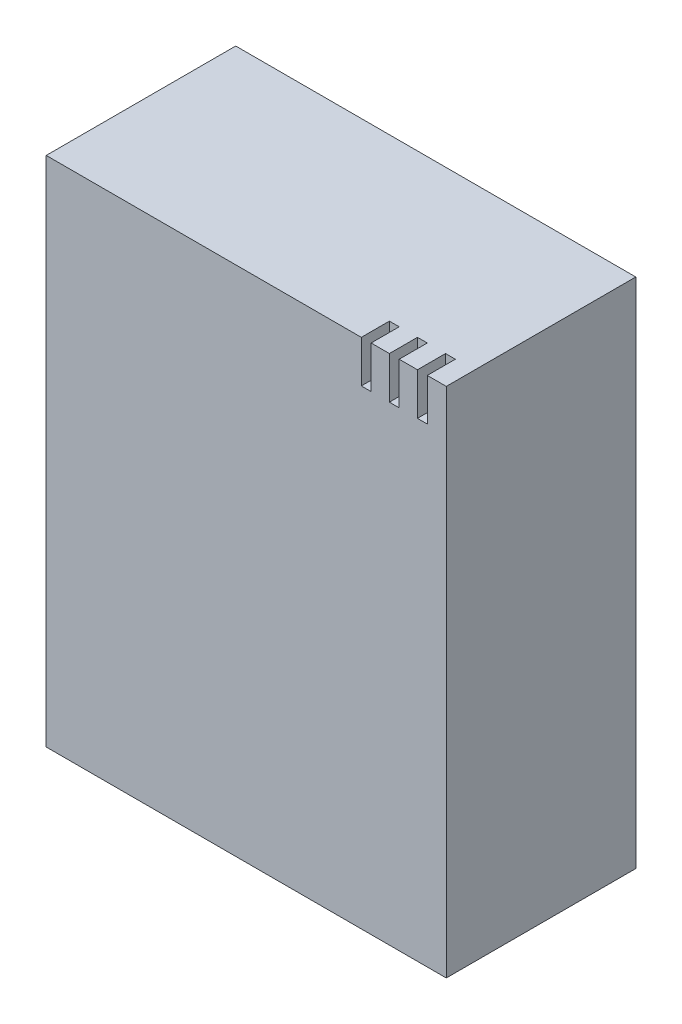
SolidWorks part; units mm, degrees
ref_plane "Front Plane" through (0, 0, 0) normal (0, 0, 1) x (1, 0, 0)
ref_plane "Top Plane" through (0, 0, 0) normal (0, 1, 0) x (1, 0, 0)
ref_plane "Right Plane" through (0, 0, 0) normal (1, 0, 0) x (0, 0, -1)
sketch "Sketch1" plane through (0, 0, 0) normal (0, 1, 0) x (1, 0, 0)
  line L1 (-14.25, -6.75) -> (14.25, -6.75)
  line L2 (-14.25, -6.75) -> (-14.25, 6.75)
  line L3 (-14.25, 6.75) -> (14.25, 6.75)
  line L4 (14.25, -6.75) -> (14.25, 6.75)
  line L5 (-14.25, -6.75) -> (14.25, 6.75) construction
  line L6 (-14.25, 6.75) -> (14.25, -6.75) construction
  point P0 (0, 0)
  dimension "D1" = 13.5
  dimension "D2" = 28.5
extrude "Boss-Extrude1" add sketch "Sketch1" along normal blind 36.5
sketch "Sketch2" plane through (0, 36.5, 0) normal (0, 1, 0) x (1, 0, 0)
  line L0 (-14.25, -6.75) -> (14.25, -6.75) construction
  line L1 (12.8962, -6.75) -> (12.1962, -6.75)
  line L2 (12.8962, -6.75) -> (12.8962, -4.75)
  line L3 (12.8962, -4.75) -> (12.1962, -4.75)
  line L4 (12.1962, -6.75) -> (12.1962, -4.75)
  line L5 (10.8962, -6.75) -> (10.8962, -4.75)
  line L6 (10.8962, -4.75) -> (10.1962, -4.75)
  line L7 (10.1962, -6.75) -> (10.1962, -4.75)
  line L8 (10.8962, -6.75) -> (10.1962, -6.75)
  line L9 (8.8962, -6.75) -> (8.8962, -4.75)
  line L10 (8.8962, -4.75) -> (8.1962, -4.75)
  line L11 (8.1962, -6.75) -> (8.1962, -4.75)
  line L12 (8.8962, -6.75) -> (8.1962, -6.75)
  dimension "D1" = 2
  dimension "D2" = 0.7
  dimension "D3" = 3
extrude "Cut-Extrude1" cut sketch "Sketch2" against normal blind 3
